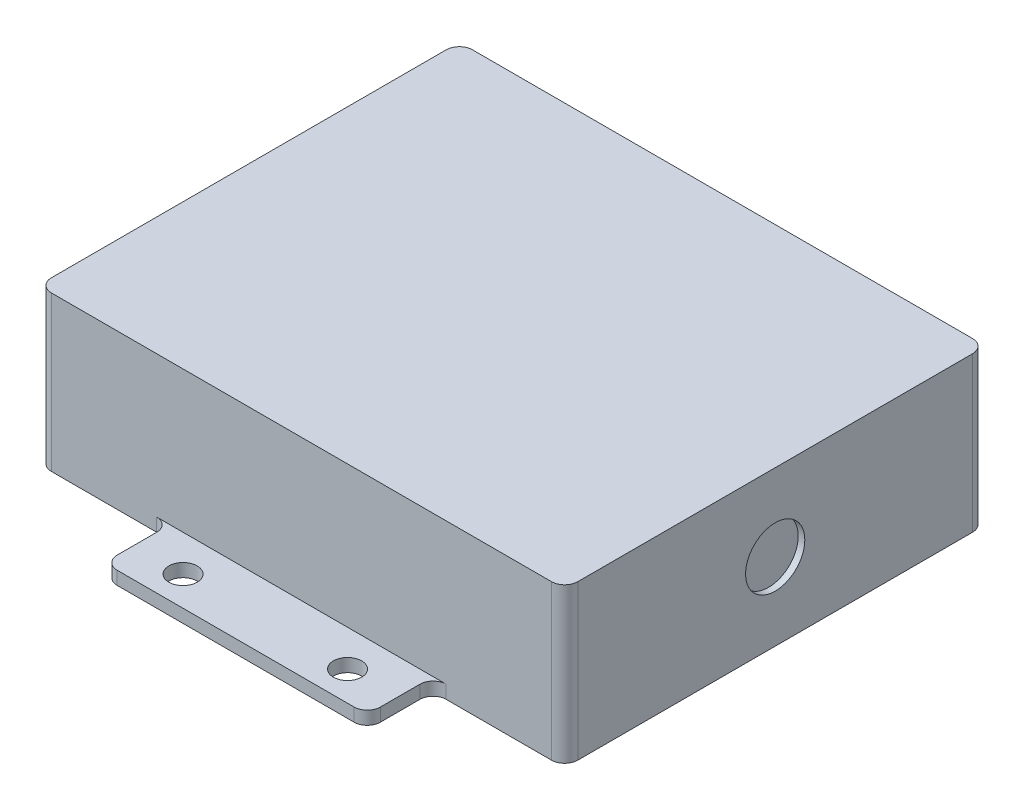
SolidWorks part; units mm, degrees
ref_plane "Front Plane" through (0, 0, 0) normal (0, 0, 1) x (1, 0, 0)
ref_plane "Top Plane" through (0, 0, 0) normal (0, 1, 0) x (1, 0, 0)
ref_plane "Right Plane" through (0, 0, 0) normal (1, 0, 0) x (0, 0, -1)
sketch "Sketch1" plane through (0, 0, 0) normal (0, 1, 0) x (1, 0, 0)
  line L1 (-40, -42) -> (40, -42)
  line L2 (-40, -42) -> (-40, 42)
  line L3 (-40, 42) -> (40, 42)
  line L4 (40, -42) -> (40, 42)
  line L5 (-40, -42) -> (40, 42) construction
  line L6 (-40, 42) -> (40, -42) construction
  point P0 (0, 0)
  dimension "D1" = 84
  dimension "D2" = 80
extrude "Boss-Extrude1" add sketch "Sketch1" along normal blind 23.5
sketch "Sketch2" plane through (0, 23.5, 0) normal (0, 1, 0) x (1, 0, 0)
  line L1 (-12.5, -37.5) -> (12.5, -37.5) construction
  line L2 (-12.5, -37.5) -> (-12.5, 37.5) construction
  line L3 (-12.5, 37.5) -> (12.5, 37.5) construction
  line L4 (12.5, -37.5) -> (12.5, 37.5) construction
  line L5 (-12.5, -37.5) -> (12.5, 37.5) construction
  line L6 (-12.5, 37.5) -> (12.5, -37.5) construction
  point P0 (0, 0)
  dimension "D1" = 75
  dimension "D2" = 25
hole_wizard "M4 Clearance Hole1" positions "Sketch3" profile "Sketch4" hole size "M4" standard "ANSI Metric" end condition through all
sketch "Sketch3" plane through (0, 23.5, 0) normal (0, 1, 0) x (1, 0, 0)
  point P0 (-12.5, 37.5)
  point P3 (12.5, 37.5)
  point P6 (-12.5, -37.5)
  point P9 (12.5, -37.5)
sketch "Sketch4" plane through (-12.5, 23.5, -37.5) normal (1, 0, 0) x (0, 0, 1)
  line L0 (0, 0) -> (0, 23.5)
  line L1 (0, 23.5) -> (2.15, 23.5)
  line L2 (2.15, 23.5) -> (2.15, 0)
  line L5 (2.15, 0) -> (0, 0)
  line L11 (0, -6.35) -> (0, 107.95) construction
  dimension "Thru Hole Dia." = 4.3
  dimension "Thru Hole Depth" = 23.5
sketch "Sketch5" plane through (-40, 0, 0) normal (-1, 0, 0) x (0, 0, 1)
  line L0 (-42, 23.5) -> (-42, 0) construction
  line L1 (-16, 7) -> (16, 7)
  line L2 (-16, 7) -> (-16, 20)
  line L3 (-16, 20) -> (16, 20)
  line L4 (16, 7) -> (16, 20)
  line L5 (-16, 7) -> (16, 20) construction
  line L6 (-16, 20) -> (16, 7) construction
  line L7 (-42, 0) -> (42, 0) construction
  point P0 (0, 13.5)
  dimension "D1" = 32
  dimension "D2" = 13
  dimension "D3" = 7
extrude "Cut-Extrude1" cut sketch "Sketch5" against normal blind 1
sketch "Sketch6" plane through (40, 0, 0) normal (1, 0, 0) x (0, 0, -1)
  line L0 (-42, 23.5) -> (-42, 0) construction
  circle A0 centre (0, 11.75) radius 4.5
  point P6 (-42, 11.75)
  dimension "D1" = 9
extrude "Cut-Extrude2" cut sketch "Sketch6" against normal blind 1
sketch "Sketch7" plane through (0, 23.5, 0) normal (0, 1, 0) x (1, 0, 0)
  line L0 (40, -42) -> (40, 42) construction
  line L1 (-40, 42) -> (40, 42)
  line L2 (-40, 42) -> (-40, 32)
  line L3 (-40, 32) -> (40, 32)
  line L4 (40, 42) -> (40, 32)
  line L5 (-40, 42) -> (-40, -42) construction
  line L6 (40, -42) -> (-40, -42)
  line L7 (40, -42) -> (40, -32)
  line L8 (40, -32) -> (-40, -32)
  line L9 (-40, -42) -> (-40, -32)
  dimension "D1" = 10
extrude "Cut-Extrude3" cut sketch "Sketch7" against normal offset from surface (21.5 mm away) 2 up to face at (-12.5, 0, -35.35)
sketch "Sketch8" plane through (0, 2, 0) normal (0, 1, 0) x (1, 0, 0)
  line L0 (-40, 32) -> (40, 32) construction
  line L1 (-40, 42) -> (-20, 42)
  line L2 (-40, 42) -> (-40, 32)
  line L3 (-40, 32) -> (-20, 32)
  line L4 (-20, 42) -> (-20, 32)
  line L5 (40, -32) -> (-40, -32) construction
  line L6 (40, 42) -> (20, 42)
  line L7 (40, 42) -> (40, 32)
  line L8 (40, 32) -> (20, 32)
  line L9 (20, 42) -> (20, 32)
  line L10 (-40, -42) -> (-20, -42)
  line L11 (-40, -42) -> (-40, -32)
  line L12 (-40, -32) -> (-20, -32)
  line L13 (-20, -42) -> (-20, -32)
  line L15 (40, -42) -> (20, -42)
  line L16 (40, -42) -> (40, -32)
  line L17 (40, -32) -> (20, -32)
  line L18 (20, -42) -> (20, -32)
  dimension "D1" = 20
extrude "Cut-Extrude4" cut sketch "Sketch8" against normal through all
fillet "Fillet1" radius 2 12 edges at (20, 1, -32) (20, 1, -42) (-20, 1, -42) (-20, 1, -32) (-40, 11.75, -32) (-40, 11.75, 32) (-20, 1, 32) (-20, 1, 42) (20, 1, 42) (20, 1, 32) (40, 11.75, -32) (40, 11.75, 32)
